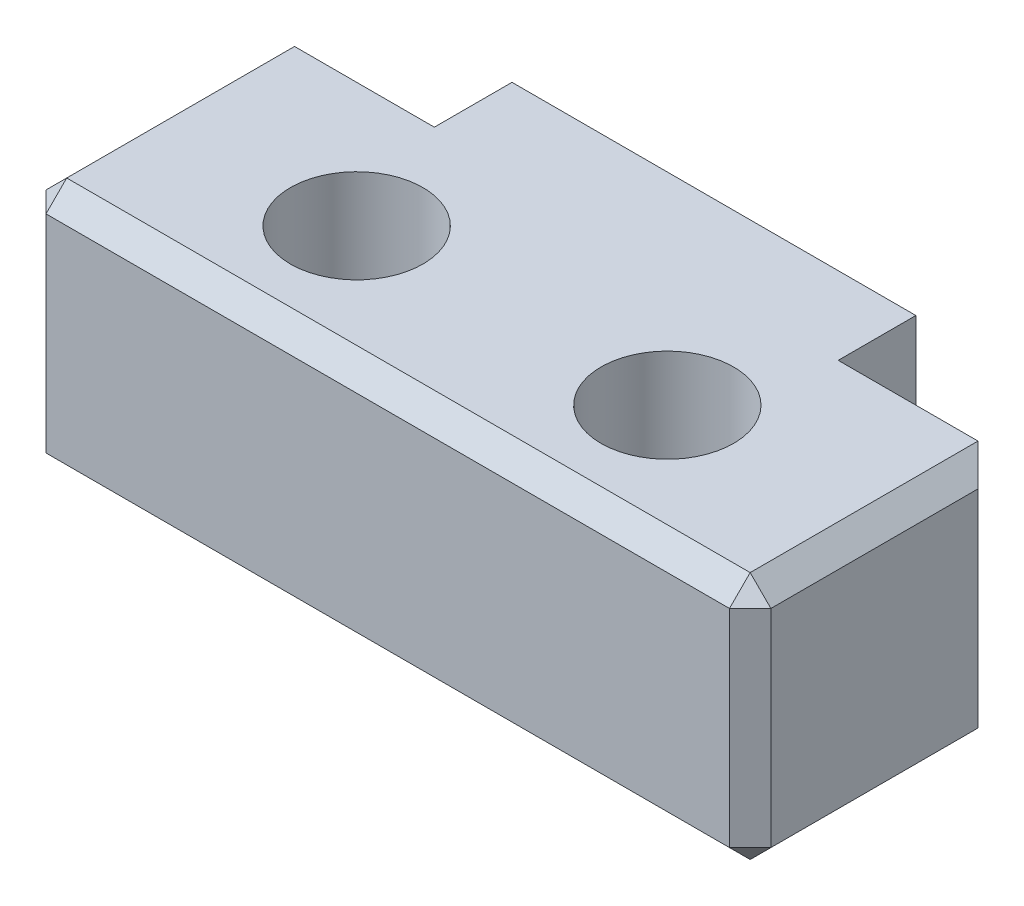
SolidWorks part; units mm, degrees
material "K110"
ref_plane "Front Plane" through (0, 0, 0) normal (0, 0, 1) x (1, 0, 0)
ref_plane "Top Plane" through (0, 0, 0) normal (0, 1, 0) x (1, 0, 0)
ref_plane "Right Plane" through (0, 0, 0) normal (1, 0, 0) x (0, 0, -1)
sketch "Sketch1" plane through (0, 0, 0) normal (0, 0, 1) x (1, 0, 0)
  line L1 (-17.5, -6) -> (17.5, -6)
  line L2 (-17.5, -6) -> (-17.5, 6)
  line L3 (-17.5, 6) -> (17.5, 6)
  line L4 (17.5, -6) -> (17.5, 6)
  line L5 (-17.5, -6) -> (17.5, 6) construction
  line L6 (-17.5, 6) -> (17.5, -6) construction
  point P0 (0, 0)
  dimension "D1" = 35
  dimension "D2" = 12
extrude "Boss-Extrude1" add sketch "Sketch1" along normal mid plane 12
sketch "Sketch3" plane through (0, 6, 0) normal (0, 1, 0) x (1, 0, 0)
  line L0 (17.5, 6) -> (-17.5, 6) construction
  line L1 (-9.75, 6) -> (9.75, 6)
  line L2 (-9.75, 6) -> (-9.75, 10.75)
  line L3 (-9.75, 10.75) -> (9.75, 10.75)
  line L4 (9.75, 6) -> (9.75, 10.75)
  point P6 (0, 6)
  dimension "D1" = 19.5
  dimension "D2" = 4.75
extrude "Boss-Extrude2" add sketch "Sketch3" against normal up to surface (12 mm away) up to face at (0, -6, 0)
sketch "Sketch4" plane through (0, 6, 0) normal (0, 1, 0) x (1, 0, 0)
  line L0 (0, -6) -> (0, 10.75) construction
  line L1 (17.5, -6) -> (-17.5, -6) construction
  line L2 (9.75, 10.75) -> (-9.75, 10.75) construction
  circle A0 centre (-7.5, 0) radius 5
  circle A1 centre (7.5, 0) radius 5
  dimension "D1" = 10
  dimension "D2" = 15
hole_wizard "M6 Clearance Hole1" positions "Sketch7" profile "Sketch6" hole size "M6" standard "ISO" end condition through all
sketch "Sketch7" plane through (0, 6, 0) normal (0, 1, 0) x (1, 0, 0)
  point P0 (-7.5, 0)
  point P3 (7.5, 0)
sketch "Sketch6" plane through (-7.5, 6, 0) normal (1, 0, 0) x (0, 0, 1)
  line L0 (0, 0) -> (0, 12)
  line L1 (0, 12) -> (3.2, 12)
  line L2 (3.2, 12) -> (3.2, 0)
  line L5 (3.2, 0) -> (0, 0)
  line L11 (0, -6.35) -> (0, 107.95) construction
  dimension "Thru Hole Dia." = 6.4
  dimension "Thru Hole Depth" = 12
chamfer "Chamfer4" distance 1 angle 45 14 edges at (0, -6, 6) (-17.5, 0, 6) (0, 6, 6) (17.5, 0, 6) (9.75, 0, -10.75) (0, -6, -10.75) (0, 6, -10.75) (-9.75, 0, -10.75) (-17.5, 6, 0) (-17.5, 0, -6) (-17.5, -6, 0) (17.5, -6, 0) (17.5, 0, -6) (17.5, 6, 0)
